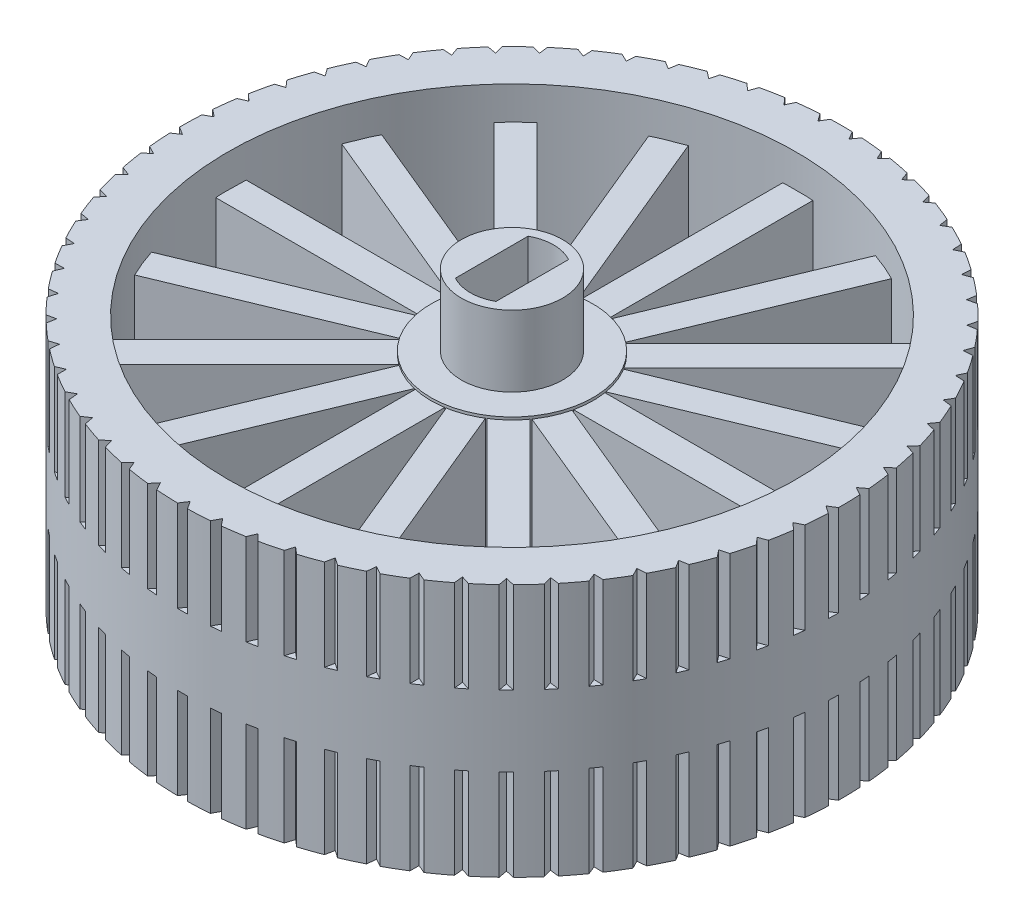
SolidWorks part; units mm, degrees
ref_plane "Front Plane" through (0, 0, 0) normal (0, 0, 1) x (1, 0, 0)
ref_plane "Top Plane" through (0, 0, 0) normal (0, 1, 0) x (1, 0, 0)
ref_plane "Right Plane" through (0, 0, 0) normal (1, 0, 0) x (0, 0, -1)
sketch "Sketch1" plane through (0, 0, 0) normal (0, 1, 0) x (1, 0, 0)
  circle A0 centre (0, 0) radius 32.5
extrude "Boss-Extrude1" add sketch "Sketch1" along normal blind 2
sketch "Sketch2" plane through (0, 2, 0) normal (0, 1, 0) x (1, 0, 0)
  circle A0 centre (0, 0) radius 4
extrude "Boss-Extrude2" add sketch "Sketch2" along normal blind 2
sketch "Sketch4" plane through (0, 4, 0) normal (0, 1, 0) x (1, 0, 0)
  line L0 (0, 4) -> (0, -4) construction
  line L1 (-4, 0) -> (-1.895, 0) construction
  line L4 (1.995, -3.5819) -> (1.995, 3.5819)
  line L5 (-1.995, 3.5819) -> (-1.995, -3.5819)
  line L7 (0, 0) -> (4, 0) construction
  circle A0 centre (0, 0) radius 4 construction
  arc A4 (1.995, 3.5819) -> (-1.995, 3.5819) centre (0, 0) ccw
  arc A5 (-1.995, -3.5819) -> (1.995, -3.5819) centre (0, 0) ccw
  point P7 (0, 0)
  point P11 (0, 0)
  point P16 (1.895, 0)
extrude "Cut-Extrude1" cut sketch "Sketch4" against normal blind 28
sketch "Sketch5" plane through (0, 2, 0) normal (0, 1, 0) x (1, 0, 0)
  circle A0 centre (0, 0) radius 8
extrude "Boss-Extrude3" add sketch "Sketch5" along normal blind 2
sketch "Sketch6" plane through (0, 2, 0) normal (0, -1, 0) x (1, 0, 0)
  line L2 (-1.995, 3.5819) -> (-1.995, -3.5819)
  line L3 (1.995, -3.5819) -> (1.995, 3.5819)
  line L4 (-1.995, 3.5819) -> (-1.995, -3.5819)
  line L5 (1.995, -3.5819) -> (1.995, 3.5819)
  arc A2 (1.995, 3.5819) -> (-1.995, 3.5819) centre (0, 0) ccw
  arc A3 (-1.995, -3.5819) -> (1.995, -3.5819) centre (0, 0) ccw
  arc A4 (1.995, 3.5819) -> (-1.995, 3.5819) centre (0, 0) ccw
  arc A5 (-1.995, -3.5819) -> (1.995, -3.5819) centre (0, 0) ccw
  dimension "D1" = 0
extrude "Cut-Extrude2" cut sketch "Sketch6" against normal through all and the other way blind 18 from offset 10
sketch "Sketch7" plane through (0, 2, 0) normal (0, 1, 0) x (1, 0, 0)
  line L0 (-1.995, -3.5819) -> (-1.995, 3.5819) construction
  line L1 (1.995, 3.5819) -> (1.995, -3.5819) construction
  line L2 (-1.995, -3.5819) -> (-1.995, 3.5819)
  line L3 (1.995, 3.5819) -> (1.995, -3.5819)
  line L4 (0, -8) -> (0, 8) construction
  line L5 (0, 8) -> (0, 28) construction
  circle A0 centre (0, 0) radius 8 construction
  circle A1 centre (0, 0) radius 8
  arc A2 (1.995, 3.5819) -> (-1.995, 3.5819) centre (0, 0) ccw construction
  arc A3 (-1.995, -3.5819) -> (1.995, -3.5819) centre (0, 0) ccw construction
  arc A4 (1.995, 3.5819) -> (-1.995, 3.5819) centre (0, 0) ccw
  arc A5 (-1.995, -3.5819) -> (1.995, -3.5819) centre (0, 0) ccw
  circle A6 centre (0, 0) radius 28
  circle A7 centre (0, 0) radius 32.5 construction
  circle A8 centre (0, 0) radius 32.5
  point P11 (0, 0)
  circle M2 centre (0, 0) radius 32.5
extrude "Boss-Extrude4" add sketch "Sketch7" along normal blind 23 contours A6 M2
sketch "Sketch9" plane through (0, 4, 0) normal (0, 1, 0) x (1, 0, 0)
  line L0 (-1.995, -3.5819) -> (-1.995, 3.5819) construction
  line L1 (1.995, 3.5819) -> (1.995, -3.5819) construction
  line L2 (-1.995, -3.5819) -> (-1.995, 3.5819)
  line L3 (1.995, 3.5819) -> (1.995, -3.5819)
  arc A0 (-1.995, -3.5819) -> (1.995, -3.5819) centre (0, 0) ccw construction
  circle A1 centre (0, 0) radius 8
  circle A2 centre (0, 0) radius 8
  arc A3 (1.995, 3.5819) -> (-1.995, 3.5819) centre (0, 0) ccw construction
  arc A4 (-1.995, -3.5819) -> (1.995, -3.5819) centre (0, 0) ccw
  arc A5 (1.995, 3.5819) -> (-1.995, 3.5819) centre (0, 0) ccw
  dimension "D1" = 0
extrude "Boss-Extrude5" add sketch "Sketch9" along normal blind 25
ref_plane "Plane1" through (-6.995, 0, 0) normal (1, 0, 0) x (0, 0, -1)
sketch "Sketch12" plane through (-6.995, 0, 0) normal (1, 0, 0) x (0, 0, -1)
  line L1 (10.471, 25) -> (-8.8085, 25) construction
  line L2 (28, 25) -> (-28, 25) construction
  line L8 (-1.2654, 21.7368) -> (1.7346, 21.7368)
  line L9 (-1.2654, 21.7368) -> (-1.2654, 2)
  line L10 (-7.6854, 2) -> (7.7278, 2) construction
  line L11 (8, 2) -> (-8, 2) construction
  line L12 (-1.2654, 2) -> (1.7346, 2)
  line L13 (1.7346, 21.7368) -> (1.7346, 2)
  line L14 (-1.2654, 21.7368) -> (1.7346, 2) construction
  line L15 (-1.2654, 2) -> (1.7346, 21.7368) construction
  point P0 (0.2346, 11.8684)
  point P11 (0.2346, 11.8684)
  dimension "D1" = 3
extrude "Boss-Extrude6" add sketch "Sketch12" against normal blind 22 separate body
pattern_circular "CirPattern2" count 16 over 360 about axis through (0, 0, 0) along (0, 1, 0) of bodies 118
sketch "Sketch13" plane through (0, 2, 0) normal (0, 1, 0) x (1, 0, 0)
  circle A1 centre (0, 0) radius 28
  circle A2 centre (0, 0) radius 28
  dimension "D1" = 0
extrude "Cut-Extrude3" cut sketch "Sketch13" against normal blind 22
sketch "Sketch14" plane through (0, 0, 0) normal (0, -1, 0) x (1, 0, 0)
  line L0 (0, 28) -> (0, 32.5) construction
  line L1 (0, 31.75) -> (-0.5277, 32.5416)
  line L6 (3.6566, 32.3357) -> (2.6154, 32.4406)
  line L7 (3.0643, 31.6018) -> (3.6566, 32.3357)
  line L8 (0, 31.75) -> (0.5187, 32.5377)
  line L9 (0.5187, 32.5377) -> (-0.5277, 32.5416)
  line L10 (3.0643, 31.6018) -> (2.6154, 32.4406)
  line L11 (6.7604, 31.8318) -> (5.7342, 32.0367)
  line L12 (6.1, 31.1585) -> (6.7604, 31.8318)
  line L13 (6.1, 31.1585) -> (5.7342, 32.0367)
  line L14 (9.8011, 31.0308) -> (8.7994, 31.3338)
  line L15 (9.0788, 30.4243) -> (9.8011, 31.0308)
  line L16 (9.0788, 30.4243) -> (8.7994, 31.3338)
  line L17 (12.7502, 29.94) -> (11.7825, 30.3382)
  line L18 (11.9728, 29.406) -> (12.7502, 29.94)
  line L19 (11.9728, 29.406) -> (11.7825, 30.3382)
  line L20 (15.5803, 28.5696) -> (14.6556, 29.0594)
  line L21 (14.755, 28.1132) -> (15.5803, 28.5696)
  line L22 (14.755, 28.1132) -> (14.6556, 29.0594)
  line L23 (18.265, 26.9325) -> (17.3918, 27.5093)
  line L24 (17.3994, 26.5579) -> (18.265, 26.9325)
  line L25 (17.3994, 26.5579) -> (17.3918, 27.5093)
  line L26 (20.779, 25.044) -> (19.9656, 25.7023)
  line L27 (19.8814, 24.7547) -> (20.779, 25.044)
  line L28 (19.8814, 24.7547) -> (19.9656, 25.7023)
  line L29 (23.0991, 22.9216) -> (22.353, 23.6554)
  line L30 (22.1777, 22.7203) -> (23.0991, 22.9216)
  line L31 (22.1777, 22.7203) -> (22.353, 23.6554)
  line L32 (25.2036, 20.5852) -> (24.5318, 21.3876)
  line L33 (24.267, 20.4737) -> (25.2036, 20.5852)
  line L34 (24.267, 20.4737) -> (24.5318, 21.3876)
  line L35 (27.0727, 18.0566) -> (26.4814, 18.92)
  line L36 (26.1297, 18.0361) -> (27.0727, 18.0566)
  line L37 (26.1297, 18.0361) -> (26.4814, 18.92)
  line L38 (28.689, 15.3594) -> (28.1838, 16.2759)
  line L39 (27.7485, 15.43) -> (28.689, 15.3594)
  line L40 (27.7485, 15.43) -> (28.1838, 16.2759)
  line L41 (30.0374, 12.5188) -> (29.6231, 13.4798)
  line L42 (29.1082, 12.6798) -> (30.0374, 12.5188)
  line L43 (29.1082, 12.6798) -> (29.6231, 13.4798)
  line L44 (31.1055, 9.5614) -> (30.7858, 10.5578)
  line L45 (30.196, 9.8113) -> (31.1055, 9.5614)
  line L46 (30.196, 9.8113) -> (30.7858, 10.5578)
  line L47 (31.8831, 6.5146) -> (31.6611, 7.5373)
  line L48 (31.002, 6.8511) -> (31.8831, 6.5146)
  line L49 (31.002, 6.8511) -> (31.6611, 7.5373)
  line L50 (32.363, 3.407) -> (32.2407, 4.4463)
  line L51 (31.5185, 3.827) -> (32.363, 3.407)
  line L52 (31.5185, 3.827) -> (32.2407, 4.4463)
  line L53 (32.5407, 0.2677) -> (32.5193, 1.3139)
  line L54 (31.7407, 0.7672) -> (32.5407, 0.2677)
  line L55 (31.7407, 0.7672) -> (32.5193, 1.3139)
  line L56 (32.4146, -2.8742) -> (32.4943, -1.8308)
  line L57 (31.6666, -2.2998) -> (32.4146, -2.8742)
  line L58 (31.6666, -2.2998) -> (32.4943, -1.8308)
  line L59 (31.9859, -5.9893) -> (32.1659, -4.9584)
  line L60 (31.2968, -5.3453) -> (31.9859, -5.9893)
  line L61 (31.2968, -5.3453) -> (32.1659, -4.9584)
  line L62 (31.2585, -9.0484) -> (31.5372, -8.0397)
  line L63 (30.6348, -8.341) -> (31.2585, -9.0484)
  line L64 (30.6348, -8.341) -> (31.5372, -8.0397)
  line L65 (30.2393, -12.023) -> (30.6141, -11.046)
  line L66 (29.6868, -11.2587) -> (30.2393, -12.023)
  line L67 (29.6868, -11.2587) -> (30.6141, -11.046)
  line L68 (28.9378, -14.8854) -> (29.4051, -13.9491)
  line L69 (28.4616, -14.0713) -> (28.9378, -14.8854)
  line L70 (28.4616, -14.0713) -> (29.4051, -13.9491)
  line L71 (27.366, -17.6088) -> (27.9215, -16.722)
  line L72 (26.9706, -16.7526) -> (27.366, -17.6088)
  line L73 (26.9706, -16.7526) -> (27.9215, -16.722)
  line L74 (25.5388, -20.1678) -> (26.1772, -19.3387)
  line L75 (25.2278, -19.2774) -> (25.5388, -20.1678)
  line L76 (25.2278, -19.2774) -> (26.1772, -19.3387)
  line L77 (23.4731, -22.5385) -> (24.1886, -21.7749)
  line L78 (23.2495, -21.6223) -> (23.4731, -22.5385)
  line L79 (23.2495, -21.6223) -> (24.1886, -21.7749)
  line L80 (21.1882, -24.6988) -> (21.9741, -24.0078)
  line L81 (21.0541, -23.7652) -> (21.1882, -24.6988)
  line L82 (21.0541, -23.7652) -> (21.9741, -24.0078)
  line L83 (18.7055, -26.6284) -> (19.5544, -26.0165)
  line L84 (18.6622, -25.6863) -> (18.7055, -26.6284)
  line L85 (18.6622, -25.6863) -> (19.5544, -26.0165)
  line L86 (16.0482, -28.3095) -> (16.9522, -27.7823)
  line L87 (16.096, -27.3675) -> (16.0482, -28.3095)
  line L88 (16.096, -27.3675) -> (16.9522, -27.7823)
  line L89 (13.241, -29.7262) -> (14.1917, -29.2888)
  line L90 (13.3795, -28.7933) -> (13.241, -29.7262)
  line L91 (13.3795, -28.7933) -> (14.1917, -29.2888)
  line L92 (10.3102, -30.8653) -> (11.2986, -30.5217)
  line L93 (10.5381, -29.9502) -> (10.3102, -30.8653)
  line L94 (10.5381, -29.9502) -> (11.2986, -30.5217)
  line L95 (7.2831, -31.7163) -> (8.3001, -31.4697)
  line L96 (7.5983, -30.8274) -> (7.2831, -31.7163)
  line L97 (7.5983, -30.8274) -> (8.3001, -31.4697)
  line L98 (4.1881, -32.2712) -> (5.2241, -32.1239)
  line L99 (4.5875, -31.4168) -> (4.1881, -32.2712)
  line L100 (4.5875, -31.4168) -> (5.2241, -32.1239)
  line L101 (1.0539, -32.5247) -> (2.0993, -32.4781)
  line L102 (1.5339, -31.7129) -> (1.0539, -32.5247)
  line L103 (1.5339, -31.7129) -> (2.0993, -32.4781)
  line L104 (-2.0901, -32.4746) -> (-1.0451, -32.5291)
  line L105 (-1.5339, -31.7129) -> (-2.0901, -32.4746)
  line L106 (-1.5339, -31.7129) -> (-1.0451, -32.5291)
  line L107 (-5.2146, -32.1213) -> (-4.1797, -32.2764)
  line L108 (-4.5875, -31.4168) -> (-5.2146, -32.1213)
  line L109 (-4.5875, -31.4168) -> (-4.1797, -32.2764)
  line L110 (-8.2904, -31.4681) -> (-7.2753, -31.7223)
  line L111 (-7.5983, -30.8274) -> (-8.2904, -31.4681)
  line L112 (-7.5983, -30.8274) -> (-7.2753, -31.7223)
  line L113 (-11.2888, -30.521) -> (-10.303, -30.872)
  line L114 (-10.5381, -29.9502) -> (-11.2888, -30.521)
  line L115 (-10.5381, -29.9502) -> (-10.303, -30.872)
  line L116 (-14.1818, -29.289) -> (-13.2345, -29.7335)
  line L117 (-13.3795, -28.7933) -> (-14.1818, -29.289)
  line L118 (-13.3795, -28.7933) -> (-13.2345, -29.7335)
  line L119 (-16.9424, -27.7835) -> (-16.0424, -28.3174)
  line L120 (-16.096, -27.3675) -> (-16.9424, -27.7835)
  line L121 (-16.096, -27.3675) -> (-16.0424, -28.3174)
  line L122 (-19.5448, -26.0186) -> (-18.7005, -26.6369)
  line L123 (-18.6622, -25.6863) -> (-19.5448, -26.0186)
  line L124 (-18.6622, -25.6863) -> (-18.7005, -26.6369)
  line L125 (-21.9647, -24.0108) -> (-21.1841, -24.7077)
  line L126 (-21.0541, -23.7652) -> (-21.9647, -24.0108)
  line L127 (-21.0541, -23.7652) -> (-21.1841, -24.7077)
  line L128 (-24.1796, -21.7788) -> (-23.4698, -22.5478)
  line L129 (-23.2495, -21.6223) -> (-24.1796, -21.7788)
  line L130 (-23.2495, -21.6223) -> (-23.4698, -22.5478)
  line L131 (-26.1687, -19.3435) -> (-25.5364, -20.1774)
  line L132 (-25.2278, -19.2774) -> (-26.1687, -19.3435)
  line L133 (-25.2278, -19.2774) -> (-25.5364, -20.1774)
  line L134 (-27.9134, -16.7275) -> (-27.3646, -17.6185)
  line L135 (-26.9706, -16.7526) -> (-27.9134, -16.7275)
  line L136 (-26.9706, -16.7526) -> (-27.3646, -17.6185)
  line L137 (-29.3975, -13.9554) -> (-28.9373, -14.8952)
  line L138 (-28.4616, -14.0713) -> (-29.3975, -13.9554)
  line L139 (-28.4616, -14.0713) -> (-28.9373, -14.8952)
  line L140 (-30.6072, -11.053) -> (-30.2398, -12.0328)
  line L141 (-29.6868, -11.2587) -> (-30.6072, -11.053)
  line L142 (-29.6868, -11.2587) -> (-30.2398, -12.0328)
  line L143 (-31.5311, -8.0474) -> (-31.26, -9.0581)
  line L144 (-30.6348, -8.341) -> (-31.5311, -8.0474)
  line L145 (-30.6348, -8.341) -> (-31.26, -9.0581)
  line L146 (-32.1606, -4.9666) -> (-31.9883, -5.9988)
  line L147 (-31.2968, -5.3453) -> (-32.1606, -4.9666)
  line L148 (-31.2968, -5.3453) -> (-31.9883, -5.9988)
  line L149 (-32.4898, -1.8395) -> (-32.4179, -2.8835)
  line L150 (-31.6666, -2.2998) -> (-32.4898, -1.8395)
  line L151 (-31.6666, -2.2998) -> (-32.4179, -2.8835)
  line L152 (-32.5156, 1.3048) -> (-32.5448, 0.2587)
  line L153 (-31.7407, 0.7672) -> (-32.5156, 1.3048)
  line L154 (-31.7407, 0.7672) -> (-32.5448, 0.2587)
  line L155 (-32.2379, 4.4369) -> (-32.3679, 3.3986)
  line L156 (-31.5185, 3.827) -> (-32.2379, 4.4369)
  line L157 (-31.5185, 3.827) -> (-32.3679, 3.3986)
  line L158 (-31.6592, 7.5276) -> (-31.8888, 6.5067)
  line L159 (-31.002, 6.8511) -> (-31.6592, 7.5276)
  line L160 (-31.002, 6.8511) -> (-31.8888, 6.5067)
  line L161 (-30.7849, 10.548) -> (-31.112, 9.554)
  line L162 (-30.196, 9.8113) -> (-30.7849, 10.548)
  line L163 (-30.196, 9.8113) -> (-31.112, 9.554)
  line L164 (-29.6231, 13.47) -> (-30.0446, 12.5121)
  line L165 (-29.1082, 12.6798) -> (-29.6231, 13.47)
  line L166 (-29.1082, 12.6798) -> (-30.0446, 12.5121)
  line L167 (-28.1848, 16.2661) -> (-28.6968, 15.3535)
  line L168 (-27.7485, 15.43) -> (-28.1848, 16.2661)
  line L169 (-27.7485, 15.43) -> (-28.6968, 15.3535)
  line L170 (-26.4833, 18.9104) -> (-27.081, 18.0514)
  line L171 (-26.1297, 18.0361) -> (-26.4833, 18.9104)
  line L172 (-26.1297, 18.0361) -> (-27.081, 18.0514)
  line L173 (-24.5346, 21.3781) -> (-25.2124, 20.5808)
  line L174 (-24.267, 20.4737) -> (-24.5346, 21.3781)
  line L175 (-24.267, 20.4737) -> (-25.2124, 20.5808)
  line L176 (-22.3567, 23.6463) -> (-23.1083, 22.9181)
  line L177 (-22.1777, 22.7203) -> (-22.3567, 23.6463)
  line L178 (-22.1777, 22.7203) -> (-23.1083, 22.9181)
  line L179 (-19.9702, 25.6936) -> (-20.7885, 25.0414)
  line L180 (-19.8814, 24.7547) -> (-19.9702, 25.6936)
  line L181 (-19.8814, 24.7547) -> (-20.7885, 25.0414)
  line L182 (-17.3972, 27.5011) -> (-18.2746, 26.9309)
  line L183 (-17.3994, 26.5579) -> (-17.3972, 27.5011)
  line L184 (-17.3994, 26.5579) -> (-18.2746, 26.9309)
  line L185 (-14.6617, 29.0517) -> (-15.5901, 28.5689)
  line L186 (-14.755, 28.1132) -> (-14.6617, 29.0517)
  line L187 (-14.755, 28.1132) -> (-15.5901, 28.5689)
  line L188 (-11.7894, 30.3312) -> (-12.76, 29.9402)
  line L189 (-11.9728, 29.406) -> (-11.7894, 30.3312)
  line L190 (-11.9728, 29.406) -> (-12.76, 29.9402)
  line L191 (-8.8069, 31.3274) -> (-9.8108, 31.0319)
  line L192 (-9.0788, 30.4243) -> (-8.8069, 31.3274)
  line L193 (-9.0788, 30.4243) -> (-9.8108, 31.0319)
  line L194 (-5.7423, 32.0312) -> (-6.77, 31.834)
  line L195 (-6.1, 31.1585) -> (-5.7423, 32.0312)
  line L196 (-6.1, 31.1585) -> (-6.77, 31.834)
  line L197 (-2.624, 32.4358) -> (-3.666, 32.3387)
  line L198 (-3.0643, 31.6018) -> (-2.624, 32.4358)
  line L199 (-3.0643, 31.6018) -> (-3.666, 32.3387)
  circle A0 centre (0, 0) radius 28 construction
  point P5 (0.0186, 32.5536)
  dimension "D1" = 65
extrude "Cut-Extrude6" cut sketch "Sketch14" against normal blind 9
ref_plane "Plane2" through (0, 12.5, 0) normal (0, 1, 0) x (1, 0, 0)
mirror "Mirror1" about plane through (0, 12.5, 0) normal (0, 1, 0) of "Cut-Extrude6"
sketch "Sketch16" plane through (0, 29, 0) normal (0, 1, 0) x (1, 0, 0)
  circle A0 centre (0, 0) radius 8 construction
  circle A1 centre (0, 0) radius 8
  circle A2 centre (0, 0) radius 5
extrude "Cut-Extrude7" cut sketch "Sketch16" against normal blind 7
